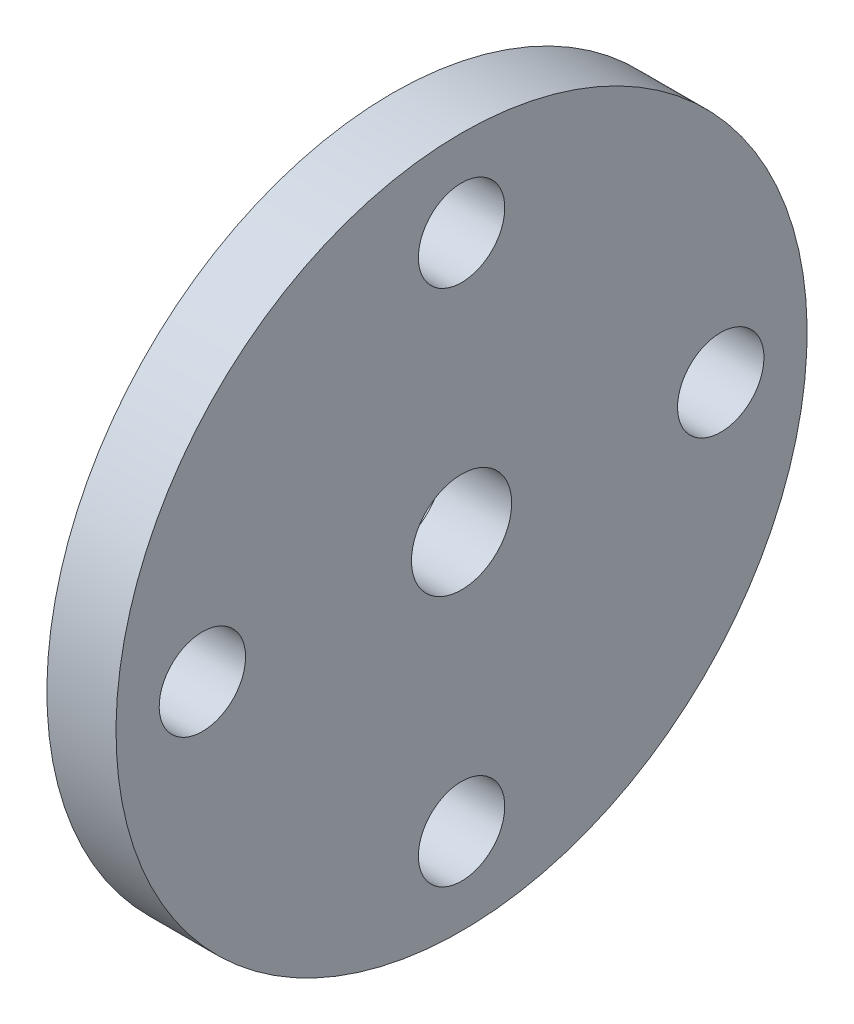
SolidWorks part; units mm, degrees
ref_plane "Plan de face" through (0, 0, 0) normal (0, 0, 1) x (1, 0, 0)
ref_plane "Plan de dessus" through (0, 0, 0) normal (0, 1, 0) x (1, 0, 0)
ref_plane "Plan de droite" through (0, 0, 0) normal (1, 0, 0) x (0, 0, -1)
sketch "Esquisse1" plane through (0, 0, 0) normal (0, 0, 1) x (1, 0, 0)
  line L0 (0, 3) -> (0, 4.7)
  line L1 (0, 4.7) -> (3, 4.7)
  line L2 (3, 4.7) -> (3, 10)
  line L3 (3, 10) -> (5, 10)
  line L4 (5, 10) -> (5, 0)
  line L5 (5, 0) -> (3, 0)
  line L6 (0, 3) -> (3, 3)
  line L7 (3, 3) -> (3, 0)
  dimension "D1" = 10
  dimension "D2" = 4.7
  dimension "D3" = 3
  dimension "D4" = 3
  dimension "D5" = 2
  dimension "D6" = 3
revolve "Révolution1" add sketch "Esquisse1" angle 360 about L5
sketch "Esquisse2" plane through (5, 0, 0) normal (1, 0, 0) x (0, 0, -1)
  circle A0 centre (0, 0) radius 1.45
  circle A1 centre (0, 7.5) radius 1.25
  circle A5 centre (7.5, 0) radius 1.25
  circle A6 centre (0, -7.5) radius 1.25
  circle A7 centre (-7.5, 0) radius 1.25
  point P14 (0.0074, 0.1238)
  point P15 (0, 0)
  dimension "D1" = 2.9
  dimension "D2" = 2.5
  dimension "D3" = 7.5
  dimension "D4" = 4
extrude "Enlèv. mat.-Extru.1" cut sketch "Esquisse2" against normal blind 10
